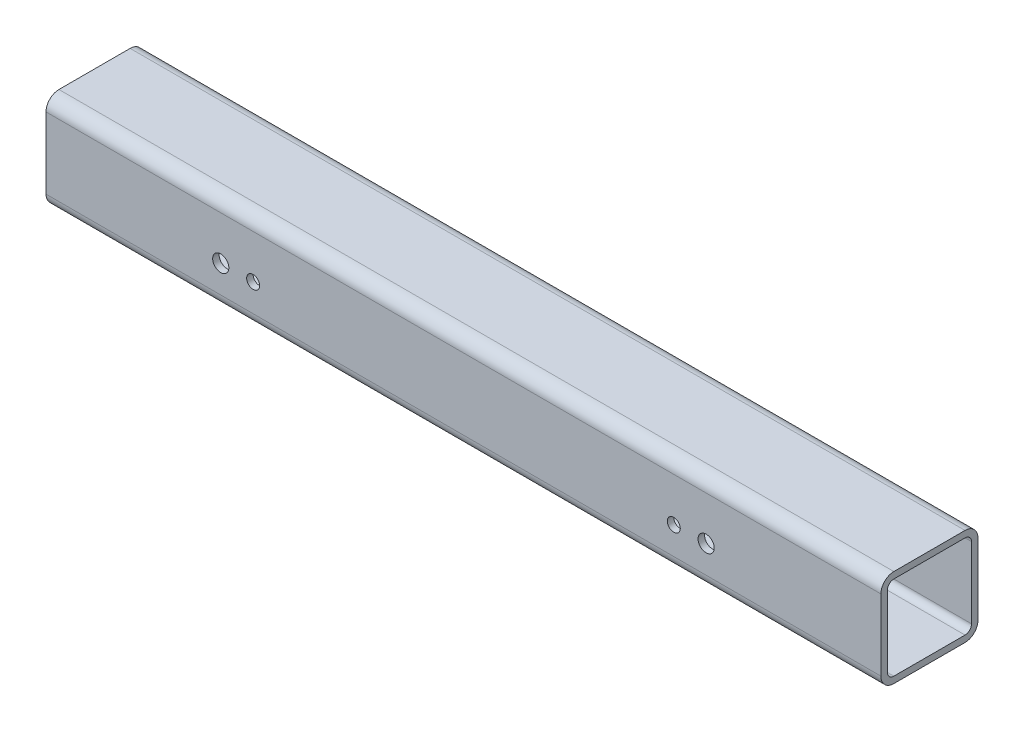
SolidWorks part; units mm, degrees
material "AISI 1010 钢，热轧条材"
ref_plane "前视基准面" through (0, 0, 0) normal (0, 0, 1) x (1, 0, 0)
ref_plane "上视基准面" through (0, 0, 0) normal (0, 1, 0) x (1, 0, 0)
ref_plane "右视基准面" through (0, 0, 0) normal (1, 0, 0) x (0, 0, -1)
sketch "草图1" plane through (0, 0, 0) normal (1, 0, 0) x (0, 0, -1)
  line L0 (-11, -13) -> (11, -13)
  line L1 (-11, -15) -> (11, -15)
  line L2 (-15, -11) -> (-15, 11)
  line L3 (-11, 15) -> (11, 15)
  line L4 (15, -11) -> (15, 11)
  line L5 (13, -11) -> (13, 11)
  line L6 (-11, 13) -> (11, 13)
  line L7 (-13, -11) -> (-13, 11)
  arc A0 (-11, -15) -> (-15, -11) centre (-11, -11) cw
  arc A1 (11, -15) -> (15, -11) centre (11, -11) ccw
  arc A2 (11, 15) -> (15, 11) centre (11, 11) cw
  arc A3 (-15, 11) -> (-11, 15) centre (-11, 11) cw
  arc A4 (11, -13) -> (13, -11) centre (11, -11) ccw
  arc A5 (11, 13) -> (13, 11) centre (11, 11) cw
  arc A6 (-13, 11) -> (-11, 13) centre (-11, 11) cw
  arc A7 (-11, -13) -> (-13, -11) centre (-11, -11) cw
extrude "凸台-拉伸1" add sketch "草图1" along normal mid plane 258
sketch "草图2" plane through (0, 0, 0) normal (0, 0, 1) x (1, 0, 0)
  line L0 (0, 15) -> (0, -15) construction
  line L1 (129, 15) -> (-129, 15) construction
  line L2 (129, -15) -> (-129, -15) construction
  circle A0 centre (-75, -2.5) radius 2.5
  circle A1 centre (75, -2.5) radius 2.5
  circle A2 centre (-65, -2.5) radius 2
  circle A3 centre (65, -2.5) radius 2
  dimension "D1" = 5
  dimension "D5" = 4
  dimension "D2" = 150
  dimension "D3" = 12.5
  dimension "D4" = 10
extrude "切除-拉伸1" cut sketch "草图2" against normal through all both and the other way through all
